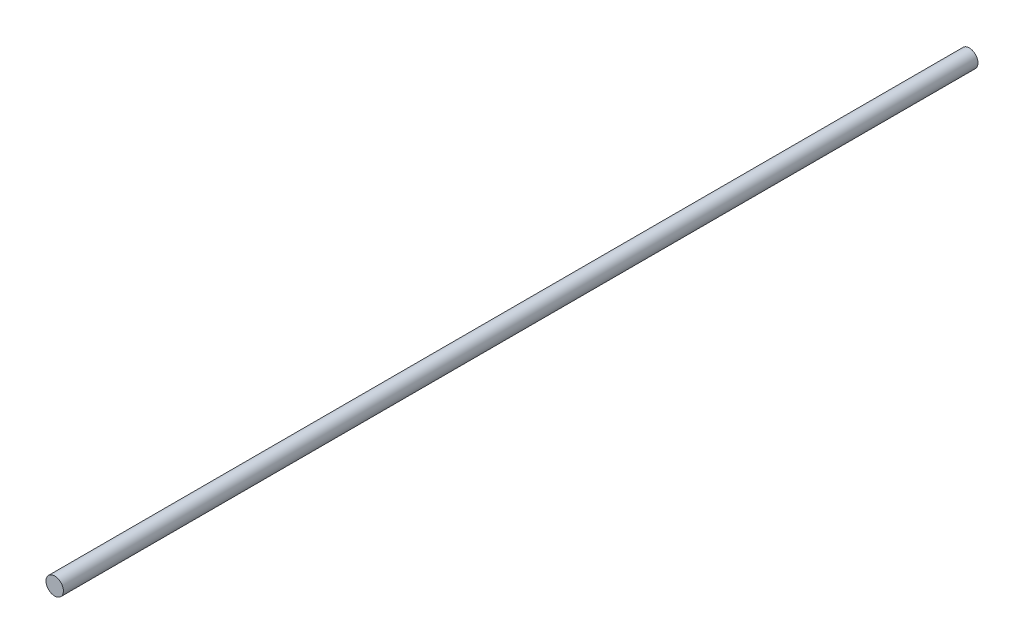
SolidWorks part; units mm, degrees
ref_plane "Front Plane" through (0, 0, 0) normal (0, 0, 1) x (1, 0, 0)
ref_plane "Top Plane" through (0, 0, 0) normal (0, 1, 0) x (1, 0, 0)
ref_plane "Right Plane" through (0, 0, 0) normal (1, 0, 0) x (0, 0, -1)
sketch "Sketch1" plane through (0, 0, 0) normal (0, 0, 1) x (1, 0, 0)
  circle A0 centre (0, 0) radius 20
  dimension "D1" = 40
extrude "Boss-Extrude9" add sketch "Sketch1" along normal blind 2100 contours A0
